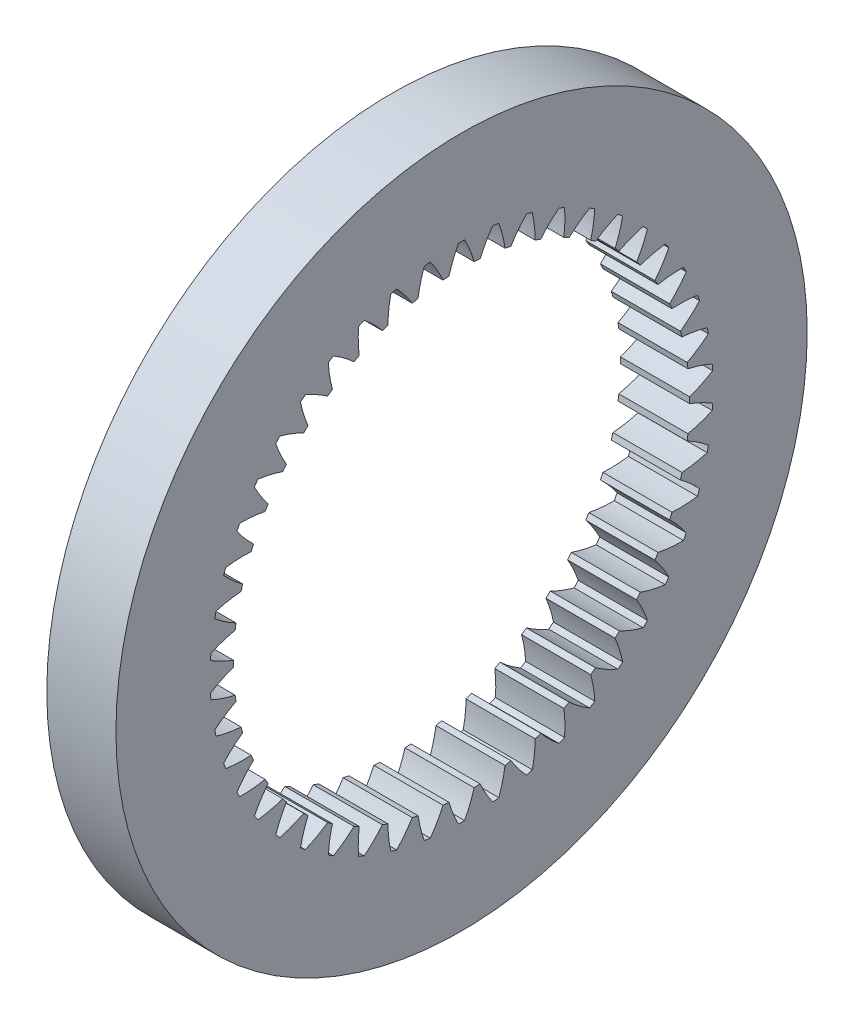
SolidWorks part; units mm, degrees
ref_plane "Plane1" through (0, 0, 0) normal (0, 0, 1) x (1, 0, 0)
ref_plane "Plane2" through (0, 0, 0) normal (0, 1, 0) x (1, 0, 0)
ref_plane "Plane3" through (0, 0, 0) normal (1, 0, 0) x (0, 0, -1)
sketch "HoldingSke" plane through (0, 0, 0) normal (0, 1, 0) x (1, 0, 0)
  line L0 (0, 0) -> (0.4631, -0.4796)
  line L1 (-15, 0) -> (100, 0) construction
  line L2 (0, 0) -> (-2.1039, 2.3779)
  line L3 (0, 0) -> (-11.863, 4.5341)
  line L4 (0, 0) -> (5.9991, 6.2122)
  line L5 (0, 0) -> (-23.7986, -8.8762)
  line L6 (0, 0) -> (-10.5278, -7.1032)
  line L7 (-2.1039, 2.3779) -> (3.3635, 27.1825)
  line L8 (-76.2, 3.8779) -> (-54.61, 3.8779)
  line L9 (-71.009, 38.7566) -> (-53.1078, 45.2721)
  line L10 (-76.2, 71.12) -> (104.1128, 71.12)
  line L11 (0, 0) -> (-10, 0)
  line L12 (-76.2, 101.6) -> (-76.147, 101.6)
  line L13 (24.9733, 27.94) -> (52.9518, 28.4284)
  line L14 (24.9733, 27.94) -> (24.9743, 27.94)
  line L15 (24.9733, 27.94) -> (100.4006, 29.5858)
  circle A0 centre (0, 0) radius 50
  circle A1 centre (0, 0) radius 12.7
  circle A2 centre (0, 0) radius 12.7
  dimension "MHD" = 25.4
  dimension "Hub_dia" = 25.4
  dimension "Diameter" = 100
  dimension "Num_teeth" = 46
  dimension "Pitch" = 0.6667
  dimension "Overall_len" = 25.4
  dimension "Show_teeth" = 46
  dimension "Thickness" = 12.7
  dimension "OAL" = 25.4001
  dimension "T_dim" = 21.59
  dimension "Ap" = 20
  dimension "H" = 19.05
  dimension "Pitch_radius" = 180.3128
  dimension "Width" = 10
  dimension "Backlash" = 0.053
  dimension "Addendum_fac" = 1
  dimension "Dedendum_fac" = 1.25
  dimension "Clearance_fac" = 0.25
  dimension "Dedendum_add" = 0.001
  dimension "Module" = 1.5
sketch "BasProSke" plane through (0, 0, 0) normal (0, 1, 0) x (1, 0, 0)
  line L0 (-10, 0) -> (60, 0) construction
  line L1 (0, 33) -> (0, 50)
  line L2 (0, 33) -> (10, 33)
  line L3 (10, 33) -> (10, 50)
  line L4 (10, 50) -> (0, 50)
  dimension "Diameter" = 100
  dimension "Thickness" = 10
  dimension "Inside_diameter" = 66
revolve "Base-Revolve" add sketch "BasProSke" angle 360 about L0
sketch "TooCutSke" plane through (0, 0, 0) normal (1, 0, 0) x (0, 0, -1)
  line L3 (1.3104, 34.4751) -> (1.3104, 53.6633) construction
  line L4 (0, 0) -> (0, 59.563) construction
  line L5 (0, 0) -> (-4.6628, 68.1682) construction
  line L6 (-14.7715, 28.2352) -> (35.7634, 31.6919) construction
  circle A0 centre (0, 0) radius 34.5 construction
  circle A1 centre (0, 0) radius 36.376 construction
  circle A2 centre (0, 0) radius 29.1775 construction
  circle A3 centre (0, 0) radius 32.9746 construction
  arc A4 (1.8291, 32.9238) -> (0.4381, 36.3734) centre (-14.7715, 28.2352) ccw
  arc A5 (1.8291, 32.9238) -> (-1.8291, 32.9238) centre (0, 0) ccw
  arc A6 (0.4381, 36.3734) -> (-0.4381, 36.3734) centre (0, 0) ccw
  arc A7 (-0.4381, 36.3734) -> (-1.8291, 32.9238) centre (14.7715, 28.2352) ccw
  dimension "Pitch_dia" = 69
  dimension "Base_dia" = 58.3549
  dimension "Root_dia" = 72.752
  dimension "Overcut_dia" = 65.9492
  dimension "Flank_rad" = 17.25
  dimension "Half_ang" = 3.913
  dimension "Half_CT" = 1.3104
extrude "ToothCut" cut sketch "TooCutSke" along normal through all
fillet "Breaks" [suppressed] radius 0.15
fillet "RootFillets" [suppressed] radius 0.376
pattern_circular "TeethCuts" count 46 every 7.826 about axis through (-10, 0, 0) along (1, 0, 0) of "RootFillets", "Breaks", "ToothCut"
sketch "Sketch1" plane through (10, 0, 0) normal (1, 0, 0) x (0, 0, -1)
  circle A0 centre (-45.7515, 0) radius 2
  circle A2 centre (0, 0) radius 50 construction
  circle A3 centre (45.752, -0.2503) radius 2
  dimension "D1" = 4
  dimension "D2" = 4
  dimension "D3" = 45.7515
equation "' \"Module@HoldingSke\" = 6.35"
equation "' \"Num_teeth@HoldingSke\" = 24"
equation "' \"Ap@HoldingSke\" =  14.5"
equation "' \"Ap@HoldingSke\" = 14.5"
equation "' \"Width@HoldingSke\" = 12"
equation "' \"Diameter@HoldingSke\" = 8 * 25.4"
equation "' \"Show_teeth@HoldingSke\" = 100"
equation "' \"Backlash@HoldingSke\" = 0.009 * 25.4"
equation "' \"Addendum_fac@HoldingSke\" = 1.0"
equation "' \"Dedendum_fac@HoldingSke\" = 1.25"
equation "' \"Dedendum_add@HoldingSke\" = 0.00005 * 25.4"
equation "' \"Clearance_fac@HoldingSke\" = 0.25"
equation "\"Pitch@HoldingSke\" = 1 / \"Module@HoldingSke\" "
equation "\"Overcut_dia@TooCutSke\" = (\"Num_teeth@HoldingSke\" - 2 * \"Addendum_fac@HoldingSke\") / \"Pitch@HoldingSke\" - 0.002 * 25.4"
equation "\"Pitch_dia@TooCutSke\" = \"Num_teeth@HoldingSke\" / \"Pitch@HoldingSke\""
equation "\"Base_dia@TooCutSke\" = \"Num_teeth@HoldingSke\" / \"Pitch@HoldingSke\" * cos((\"Ap@HoldingSke\"  * 3.14159265 / 180)) * 0.90"
equation "\"Root_dia@TooCutSke\" = \"Num_teeth@HoldingSke\"  / \"Pitch@HoldingSke\" + 2 *  \"Dedendum_fac@HoldingSke\"/ \"Pitch@HoldingSke\" + \"Dedendum_add@HoldingSke\" * 2"
equation "\"Half_ang@TooCutSke\" = 180 / \"Num_teeth@HoldingSke\""
equation "\"Half_CT@TooCutSke\" = \"Num_teeth@HoldingSke\" / \"Pitch@HoldingSke\" * sin((3.14159265 / 2 / \"Num_teeth@HoldingSke\")) / 2 + 10 * \"Backlash@HoldingSke\" / 4"
equation "\"Flank_rad@TooCutSke\" = \"Num_teeth@HoldingSke\" / \"Pitch@HoldingSke\" / 4"
equation "\"Radius@RootFillets\"= \"Clearance_fac@HoldingSke\" / \"Pitch@HoldingSke\" + \"Dedendum_add@HoldingSke\""
equation "\"Break_rad@Breaks\" = 0.02 / \"Pitch@HoldingSke\" * 5"
equation "\"Num_teeth@TeethCuts\" = int( \"Show_teeth@HoldingSke\" ) + 1"
equation "\"Num_teeth@TeethCuts\" = ((sgn( \"Num_teeth@TeethCuts\" - \"Num_teeth@HoldingSke\" )-1)*( \"Num_teeth@TeethCuts\" - \"Num_teeth@HoldingSke\" ))/-2+ \"Num_teeth@HoldingSke\""
equation "\"Num_teeth@TeethCuts\" = ((sgn( \"Num_teeth@TeethCuts\" - 2.0)+1)*( \"Num_teeth@TeethCuts\" - 2.0))/2 +2.0"
equation "\"Angle@TeethCuts\" = 360.0 / \"Num_teeth@HoldingSke\""
equation "\"Diameter@BasProSke\" = \"Num_teeth@HoldingSke\"  / \"Pitch@HoldingSke\" + 2 *  \"Dedendum_fac@HoldingSke\"/ \"Pitch@HoldingSke\" + \"Dedendum_add@HoldingSke\" * 2 + 0.002 * 25.4"
equation "\"Diameter@BasProSke\" = ((sgn( \"Diameter@BasProSke\"  - \"Diameter@HoldingSke\" )+1)*( \"Diameter@BasProSke\"  - \"Diameter@HoldingSke\" ))/2 + \"Diameter@HoldingSke\""
equation "\"Inside_diameter@BasProSke\" =  (\"Num_teeth@HoldingSke\" - 2 * \"Addendum_fac@HoldingSke\") / \"Pitch@HoldingSke\" "
equation "\"Thickness@BasProSke\"  = \"Width@HoldingSke\""
